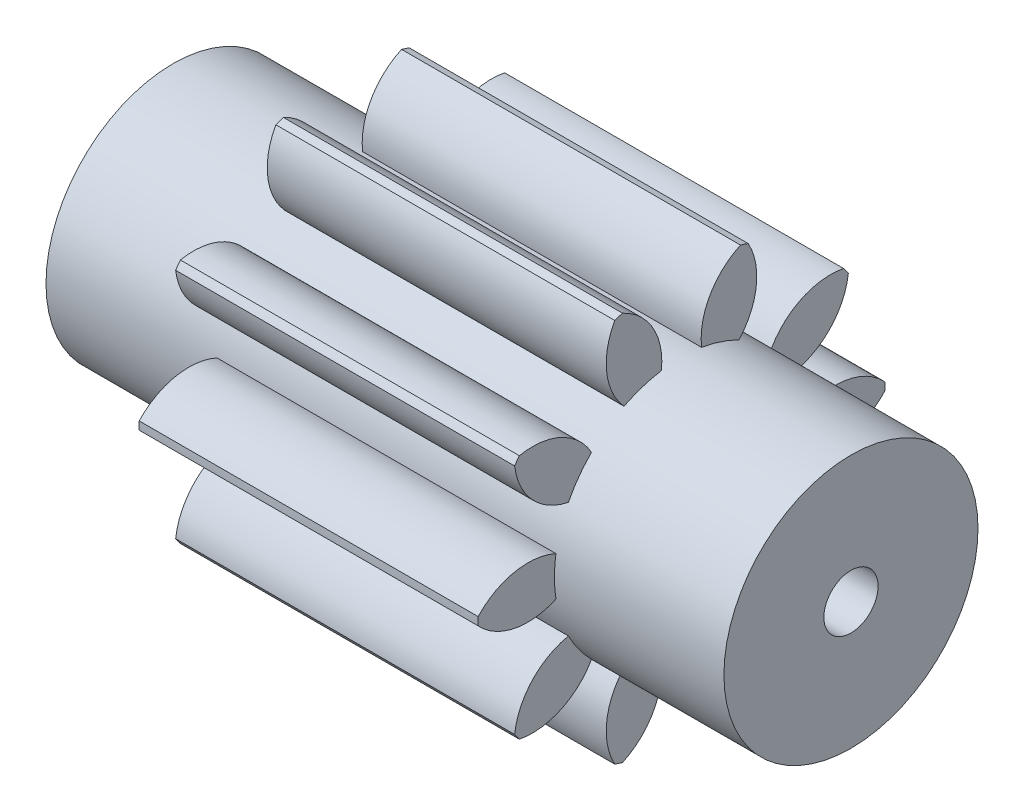
SolidWorks part; units mm, degrees
ref_plane "Plane1" through (0, 0, 0) normal (0, 0, 1) x (1, 0, 0)
ref_plane "Plane2" through (0, 0, 0) normal (0, 1, 0) x (1, 0, 0)
ref_plane "Plane3" through (0, 0, 0) normal (1, 0, 0) x (0, 0, -1)
other "Configuration Table"
sketch "HoldingSke" plane through (0, 0, 0) normal (0, 1, 0) x (1, 0, 0)
  line L0 (0, 0) -> (1.9696, -0.3473)
  line L1 (-15, 0) -> (100, 0) construction
  line L2 (0, 0) -> (-2.1039, 2.3779)
  line L3 (0, 0) -> (-11.863, 4.5341)
  line L4 (0, 0) -> (8.5048, 1.4996)
  line L5 (0, 0) -> (-9.3695, -3.4946)
  line L6 (0, 0) -> (-4.1448, -2.7965)
  line L7 (-2.1039, 2.3779) -> (0.0486, 12.1435)
  line L8 (-76.2, 54.61) -> (-76.1, 54.61)
  line L9 (-71.009, 38.7566) -> (-53.1078, 45.2721)
  line L10 (-76.2, 71.12) -> (104.1128, 71.12)
  line L11 (0, 0) -> (-5, 0)
  line L12 (-76.2, 101.6) -> (-76.181, 101.6)
  line L13 (24.9733, 27.94) -> (52.9518, 28.4284)
  line L14 (24.9733, 27.94) -> (24.9743, 27.94)
  line L15 (24.9733, 27.94) -> (100.4006, 29.5858)
  line L16 (-63.627, -0.5) -> (-12.827, -0.5)
  circle A0 centre (0, 0) radius 0.4
  circle A1 centre (0, 0) radius 1.874
  circle A2 centre (0, 0) radius 37.5
  circle A3 centre (0, 0) radius 0.4
  dimension "MHD" = 3.748
  dimension "Hub_dia" = 75
  dimension "Bore" = 0.8
  dimension "MBD" = 0.8
  dimension "Num_teeth" = 10
  dimension "Pitch" = 2
  dimension "Overall_len" = 10
  dimension "Show_teeth" = 10
  dimension "Thickness" = 5
  dimension "OAL" = 10.0001
  dimension "T_dim" = 0.1
  dimension "Ap" = 20
  dimension "H" = 19.05
  dimension "Pitch_radius" = 180.3128
  dimension "Width" = 5
  dimension "Backlash" = 0.019
  dimension "Addendum_fac" = 1
  dimension "Dedendum_fac" = 1.25
  dimension "Clearance_fac" = 0.25
  dimension "Dedendum_add" = 0.001
  dimension "Module" = 0.5
sketch "BasProSke" plane through (0, 0, 0) normal (0, 1, 0) x (1, 0, 0)
  line L0 (-10, 0) -> (60, 0) construction
  line L1 (0, 0) -> (0, 3)
  line L2 (0, 0) -> (5, 0)
  line L3 (5, 0) -> (5, 3)
  line L4 (5, 3) -> (0, 3)
  dimension "Thickness" = 5
  dimension "Diameter" = 6
revolve "Base-Revolve" add sketch "BasProSke" angle 360 about L0
sketch "TooCutSke" plane through (0, 0, 0) normal (1, 0, 0) x (0, 0, -1)
  line L1 (0, 0) -> (0, 107) construction
  line L2 (0, 0) -> (-0.4243, 2.4637) construction
  line L3 (0, 0) -> (-1.5292, 4.7063) construction
  line L4 (-0.4243, 2.4637) -> (-0.7646, 2.3532) construction
  arc A0 (0.2964, 1.8504) -> (-0.2964, 1.8504) centre (0, 0) ccw
  arc A1 (0.9059, 2.8866) -> (-0.9059, 2.8866) centre (0, 0) ccw
  circle A2 centre (0, 0) radius 2.5 construction
  circle A3 centre (0, 0) radius 2.3492 construction
  arc A4 (-0.2964, 1.8504) -> (-0.9059, 2.8866) centre (-1.2901, 1.9633) ccw
  arc A5 (0.9059, 2.8866) -> (0.2964, 1.8504) centre (1.2901, 1.9633) ccw
  dimension "Root_dia" = 3.748
  dimension "Overcut_dia" = 6.0508
  dimension "Pitch_dia" = 5
  dimension "Base_dia" = 4.6985
  dimension "Flank_rad" = 1
  dimension "Half_ang" = 18
  dimension "Half_CT" = 0.3578
extrude "ToothCut" cut sketch "TooCutSke" along normal through all
fillet "Breaks" [suppressed] radius 0.01
fillet "RootFillets" [suppressed] radius 0.126
pattern_circular "TeethCuts" count 10 every 36 about axis through (-10, 0, 0) along (1, 0, 0) of "ToothCut", "RootFillets", "Breaks"
sketch "HubNeaOneSke" plane through (0, 0, 0) normal (-1, 0, 0) x (0, 0, 1)
  circle A0 centre (0, 0) radius 1.874
  dimension "Diameter" = 3.748
extrude "HubNearOne" [suppressed] add sketch "HubNeaOneSke" along normal blind 5.0001
sketch "HubNeaBotSke" plane through (0, 0, 0) normal (-1, 0, 0) x (0, 0, 1)
  circle A0 centre (0, 0) radius 1.874
  dimension "Diameter" = 3.748
extrude "HubNearBoth" add sketch "HubNeaBotSke" along normal blind 2.5
ref_plane "FarPln" through (5, 0, 0) normal (1, 0, 0) x (0, 0, -1)
sketch "HubFarSke" plane through (5, 0, 0) normal (1, 0, 0) x (0, 0, -1)
  circle A0 centre (0, 0) radius 1.874
  dimension "Diameter" = 3.748
extrude "HubFar" add sketch "HubFarSke" along normal blind 2.5
sketch "BorSke" plane through (0, 0, 0) normal (1, 0, 0) x (0, 0, -1)
  circle A0 centre (0, 0) radius 0.4
  dimension "Diameter" = 0.8
extrude "Bore" cut sketch "BorSke" along normal mid plane 20.0001
sketch "KeySke" plane through (0, 0, 0) normal (1, 0, 0) x (0, 0, -1)
  line L0 (-0.05, 0) -> (-0.05, 0.5)
  line L1 (-0.05, 0.5) -> (0.05, 0.5)
  line L2 (0.05, 0.5) -> (0.05, 0)
  line L3 (0, 0) -> (0, 34) construction
  line L4 (-0.05, 0) -> (0.05, 0)
  dimension "Offset" = 0.5
  dimension "Width" = 0.1
extrude "Keyway" [suppressed] cut sketch "KeySke" along normal mid plane 20.0001
pattern_circular "Keyway2" [suppressed] count 2 every 90 about axis through (-10, 0, 0) along (1, 0, 0)
equation "' \"Module@HoldingSke\" = 6.35"
equation "' \"Num_teeth@HoldingSke\" = 12"
equation "' \"Ap@HoldingSke\" =  20"
equation "' \"Ap@HoldingSke\" = 20"
equation "' \"Width@HoldingSke\" = 0.5 * 25.4"
equation "' \"Hub_dia@HoldingSke\"= 1 * 25.4"
equation "' \"Hub_dia@HoldingSke\" = 1 * 25.4"
equation "' \"Overall_len@HoldingSke\" = 1.0 * 25.4"
equation "' \"Bore@HoldingSke\" = 0.75 * 25.4"
equation "' \"T_dim@HoldingSke\" = 0.1 * 25.4"
equation "' \"Width@KeySke\" = 0.25 * 25.4"
equation "' \"Show_teeth@HoldingSke\" = 13"
equation "' \"Backlash@HoldingSke\" = 0.009 * 25.4"
equation "' \"Addendum_fac@HoldingSke\" = 1.0"
equation "' \"Dedendum_fac@HoldingSke\" = 1.25"
equation "' \"Dedendum_add@HoldingSke\" = 0.00005 * 25.4"
equation "' \"Clearance_fac@HoldingSke\" = 0.25"
equation "\"Pitch@HoldingSke\" = 1 / \"Module@HoldingSke\""
equation "\"Overcut_dia@TooCutSke\" = (\"Num_teeth@HoldingSke\" + 2 * \"Addendum_fac@HoldingSke\") / \"Pitch@HoldingSke\" + 0.002 * 25.4"
equation "\"Pitch_dia@TooCutSke\" = \"Num_teeth@HoldingSke\" / \"Pitch@HoldingSke\""
equation "\"Base_dia@TooCutSke\" = \"Num_teeth@HoldingSke\" / \"Pitch@HoldingSke\" * cos((\"Ap@HoldingSke\"  * 3.14159265 / 180))"
equation "\"Root_dia@TooCutSke\" = (\"Num_teeth@HoldingSke\" + 2) / \"Pitch@HoldingSke\" - 2 * (\"Addendum_fac@HoldingSke\" + \"Dedendum_fac@HoldingSke\") / \"Pitch@HoldingSke\" - \"Dedendum_add@HoldingSke\" * 2"
equation "\"Half_ang@TooCutSke\" = 180 / \"Num_teeth@HoldingSke\""
equation "\"Half_CT@TooCutSke\" = \"Num_teeth@HoldingSke\" / \"Pitch@HoldingSke\" * sin((3.14159265 / 2 / \"Num_teeth@HoldingSke\")) / 2 - 7 * \"Backlash@HoldingSke\" / 4"
equation "\"Flank_rad@TooCutSke\" = \"Num_teeth@HoldingSke\" / \"Pitch@HoldingSke\" / 5"
equation "\"Radius@RootFillets\" = \"Clearance_fac@HoldingSke\" / \"Pitch@HoldingSke\" + \"Dedendum_add@HoldingSke\""
equation "\"Break_rad@Breaks\" = 0.02 / \"Pitch@HoldingSke\""
equation "\"Thickness@HoldingSke\" = \"Width@HoldingSke\""
equation "\"OAL@HoldingSke\" = \"Thickness@HoldingSke\""
equation "\"MHD@HoldingSke\" = (\"Num_teeth@HoldingSke\" + 2) / \"Pitch@HoldingSke\" - 2 * (\"Addendum_fac@HoldingSke\" + \"Dedendum_fac@HoldingSke\")  / \"Pitch@HoldingSke\" - \"Dedendum_add@HoldingSke\" * 2"
equation "\"MBD@HoldingSke\" = (\"Num_teeth@HoldingSke\" + 2) / \"Pitch@HoldingSke\" - 2 * (\"Addendum_fac@HoldingSke\" + \"Dedendum_fac@HoldingSke\")  / \"Pitch@HoldingSke\" - \"Dedendum_add@HoldingSke\" * 2 - 0.002 * 25.4"
equation "\"MHD@HoldingSke\" = ((sgn( \"MHD@HoldingSke\" - \"Hub_dia@HoldingSke\" )-1)*( \"MHD@HoldingSke\" - \"Hub_dia@HoldingSke\" ))/-2+ \"Hub_dia@HoldingSke\""
equation "\"MBD@HoldingSke\" = ((sgn( \"MBD@HoldingSke\" - \"Bore@HoldingSke\" )-1)*( \"MBD@HoldingSke\" - \"Bore@HoldingSke\" ))/-2+ \"Bore@HoldingSke\""
equation "\"OAL@HoldingSke\" = ((sgn( \"OAL@HoldingSke\" - \"Overall_len@HoldingSke\" )+1)*( \"OAL@HoldingSke\" - \"Overall_len@HoldingSke\" ))/2 + \"Overall_len@HoldingSke\" + 0.000002 * 25.4"
equation "\"Num_teeth@TeethCuts\" = int( \"Show_teeth@HoldingSke\" ) + 1"
equation "\"Num_teeth@TeethCuts\" = ((sgn( \"Num_teeth@TeethCuts\" - \"Num_teeth@HoldingSke\" )-1)*( \"Num_teeth@TeethCuts\" - \"Num_teeth@HoldingSke\" ))/-2+ \"Num_teeth@HoldingSke\""
equation "\"Num_teeth@TeethCuts\" = ((sgn( \"Num_teeth@TeethCuts\" - 2.0)+1)*( \"Num_teeth@TeethCuts\" - 2.0))/2 +2.0"
equation "\"Angle@TeethCuts\" = 360.0 / \"Num_teeth@HoldingSke\""
equation "\"Diameter@BasProSke\" = (\"Num_teeth@HoldingSke\" + 2 * \"Addendum_fac@HoldingSke\") / \"Pitch@HoldingSke\""
equation "\"Thickness@BasProSke\"  = \"Thickness@HoldingSke\""
equation "' \"Fillet_rad@BasProSke\" =  \"Thickness@HoldingSke\" * 0.05"
equation "' \"Fillet_rad@BasProSke\" = \"Thickness@HoldingSke\" * 0.05"
equation "\"MHD@HoldingSke\" = ((sgn( \"MHD@HoldingSke\" - \"Root_dia@TooCutSke\" )-1)*( \"MHD@HoldingSke\" - \"Root_dia@TooCutSke\" ))/-2+ \"Root_dia@TooCutSke\""
equation "\"Diameter@HubNeaOneSke\" = \"MHD@HoldingSke\""
equation "\"Length@HubNearOne\" = \"OAL@HoldingSke\" - \"Thickness@BasProSke\""
equation "\"Diameter@HubNeaBotSke\" = \"MHD@HoldingSke\""
equation "\"Length@HubNearBoth\" = ( \"OAL@HoldingSke\" - \"Thickness@BasProSke\" ) / 2.0"
equation "\"Thickness@FarPln\" = \"Thickness@BasProSke\""
equation "\"Diameter@HubFarSke\" = \"MHD@HoldingSke\""
equation "\"Length@HubFar\" = ( \"OAL@HoldingSke\" - \"Thickness@BasProSke\" ) / 2.0"
equation "\"Diameter@BorSke\" = \"MBD@HoldingSke\""
equation "\"D1@Bore\" = \"OAL@HoldingSke\" * 2.0"
equation "\"D1@Keyway\" = \"OAL@HoldingSke\" * 2.0"
equation "\"Offset@KeySke\" = \"T_dim@HoldingSke\" + \"MBD@HoldingSke\" / 2.0"
